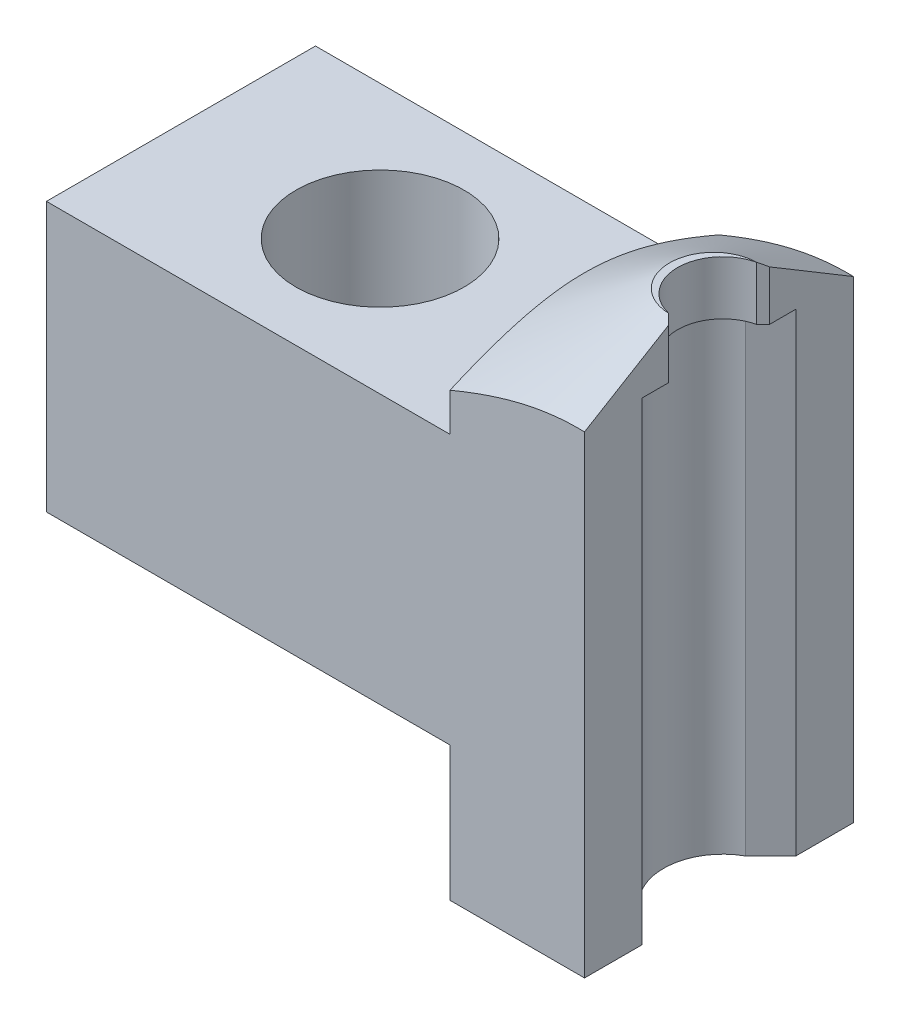
SolidWorks part; units mm, degrees
material "O1 Steel"
ref_plane "Alzado" through (0, 0, 0) normal (0, 0, 1) x (1, 0, 0)
ref_plane "Planta" through (0, 0, 0) normal (0, 1, 0) x (1, 0, 0)
ref_plane "Vista lateral" through (0, 0, 0) normal (1, 0, 0) x (0, 0, -1)
sketch "Croquis1" plane through (0, 0, 0) normal (0, 0, 1) x (1, 0, 0)
  line L0 (-9.525, 6.35) -> (-9.525, -6.35)
  line L1 (-9.525, -6.35) -> (9.525, -6.35)
  line L2 (9.525, -6.35) -> (9.525, -12.7)
  line L3 (9.525, -12.7) -> (15.875, -12.7)
  line L4 (15.875, -12.7) -> (15.875, 12.192)
  line L5 (15.875, 12.192) -> (9.525, 12.192)
  line L7 (9.525, 12.192) -> (9.525, 6.35)
  line L8 (9.525, 6.35) -> (-9.525, 6.35)
  line L9 (-9.525, 0) -> (0, 0) construction
  line L11 (0, 6.35) -> (0, 0) construction
  dimension "D1" = 12.7
  dimension "D2" = 6.35
  dimension "D3" = 25.4
  dimension "D4" = 19.05
  dimension "D7" = 18.542
extrude "Saliente-Extruir1" add sketch "Croquis1" against normal blind 12.7
sketch "Croquis2" plane through (0, 6.35, 0) normal (0, 1, 0) x (1, 0, 0)
  line L0 (-0.127, 6.35) -> (-9.525, 6.35) construction
  line L1 (-9.525, 12.7) -> (-9.525, 0) construction
  line L3 (15.875, 12.7) -> (15.875, 0) construction
  point P0 (-0.127, 6.35)
  dimension "D1" = 16.002
hole_wizard "Refrentado para tornillo con cabeza hueca de #101" positions "Croquis2" profile "Croquis3" counterbore size "#10" standard "Ansi Inch" end condition through all
sketch "Croquis3" plane through (-0.127, 6.35, -6.35) normal (1, 0, 0) x (0, 0, 1)
  line L0 (0, 0) -> (0, 19.05)
  line L1 (0, 19.05) -> (2.5527, 19.05)
  line L3 (2.5527, 19.05) -> (2.5527, 6.35)
  line L4 (2.5527, 6.35) -> (3.9687, 6.35)
  line L5 (3.9687, 6.35) -> (3.9688, 0)
  line L7 (3.9688, 0) -> (0, 0)
  line L11 (0, -6.35) -> (0, 107.95) construction
  dimension "Diámetro de taladro hasta el siguiente" = 5.1054
  dimension "Profundidad de taladro hasta el siguiente" = 19.05
  dimension "Diámetro de refrentado" = 7.9375
  dimension "Profundidad de refrentado" = 6.35
sketch "Croquis6" plane through (0, -12.7, 0) normal (0, -1, 0) x (-1, 0, 0)
  line L0 (-16.0528, 6.35) -> (0.127, 6.35) construction
  line L2 (9.525, 12.7) -> (9.525, 0) construction
  point P0 (-16.0528, 6.35)
  dimension "D1" = 25.5778
hole_wizard "Refrentado para tornillo con cabeza hueca de #61" positions "Croquis6" profile "Croquis7" counterbore size "#6" standard "Ansi Inch" end condition through all
sketch "Croquis7" plane through (16.0528, -12.7, -6.35) normal (1, 0, 0) x (0, 0, -1)
  line L0 (0, 0) -> (0, 24.892)
  line L1 (0, 24.892) -> (2.1336, 24.892)
  line L3 (2.1336, 24.892) -> (2.1336, 22.352)
  line L4 (2.1336, 22.352) -> (2.794, 22.352)
  line L5 (2.794, 22.352) -> (2.794, 0)
  line L7 (2.794, 0) -> (0, 0)
  line L11 (0, -6.35) -> (0, 107.95) construction
  dimension "Diámetro de taladro hasta el siguiente" = 4.2672
  dimension "Profundidad de taladro hasta el siguiente" = 24.892
  dimension "Diámetro de refrentado" = 5.588
  dimension "Profundidad de refrentado" = 22.352
sketch "Croquis12" plane through (0, -12.7, 0) normal (0, -1, 0) x (1, 0, 0)
  line L0 (15.875, -9.978) -> (14.6812, -8.7842)
  line L1 (15.875, -12.7) -> (15.875, -9.1383) construction
  line L2 (14.6812, -8.7842) -> (15.875, -8.7842)
  line L3 (15.875, -9.1383) -> (15.875, -8.4762) construction
  line L4 (15.875, -8.7842) -> (15.875, -9.978)
  line L5 (13.2588, -6.35) -> (-0.127, -6.35) construction
  line L6 (15.875, -3.9158) -> (15.875, -2.722)
  line L7 (14.6812, -3.9158) -> (15.875, -3.9158)
  line L8 (15.875, -2.722) -> (14.6812, -3.9158)
  arc A0 (15.875, -3.5617) -> (15.875, -9.1383) centre (16.0528, -6.35) ccw construction
  arc A1 (15.875, -3.5617) -> (15.875, -9.1383) centre (16.0528, -6.35) ccw construction
  dimension "D1" = 1.1938
  dimension "D2" = 135
extrude "Cortar-Extruir4" cut sketch "Croquis12" against normal up to surface (22.352 mm away) up to face at (14.732, 9.652, -6.35)
sketch "Croquis13" plane through (0, -12.7, 0) normal (0, -1, 0) x (1, 0, 0)
  line L4 (15.875, -3.9669) -> (15.5702, -4.2717)
  line L5 (15.875, -4.2238) -> (15.875, -2.722) construction
  line L6 (15.5702, -4.2717) -> (15.875, -4.2717)
  line L7 (15.875, -4.2717) -> (15.875, -3.9669)
  line L8 (13.9192, -6.35) -> (-0.127, -6.35) construction
  line L9 (15.875, -8.4283) -> (15.875, -8.7331)
  line L10 (15.5702, -8.4283) -> (15.875, -8.4283)
  line L11 (15.875, -8.7331) -> (15.5702, -8.4283)
  arc A1 (15.875, -4.2238) -> (15.875, -8.4762) centre (16.0528, -6.35) ccw construction
  dimension "D1" = 0.3048
  dimension "D2" = 135
extrude "Cortar-Extruir5" cut sketch "Croquis13" against normal through all
ref_plane "Plano1" through (0, 0, -6.35) normal (0, 0, 1) x (1, 0, 0)
sketch "Croquis21" plane through (0, 0, -6.35) normal (0, 0, 1) x (1, 0, 0)
  line L0 (13.5382, 12.192) -> (5.6007, 7.4227)
  line L2 (15.875, -12.7) -> (15.875, 12.192) construction
  line L3 (5.6007, 7.4227) -> (5.6007, 12.192)
  line L4 (5.6007, 12.192) -> (13.5382, 12.192)
  line L5 (15.621, 12.192) -> (15.621, -0.508) construction
  line L6 (15.875, 12.192) -> (9.525, 12.192) construction
  dimension "D1" = 2.3368
  dimension "D2" = 2.0828
  dimension "D3" = 12.7
  dimension "D4" = 31
revolve "Cortar-Revolución12" cut sketch "Croquis21" angle 360 about L5
sketch "Croquis5" plane through (15.875, 0, 0) normal (1, 0, 0) x (0, 0, -1)
  line L1 (8.4727, 12.192) -> (12.7, 9.652)
  line L2 (12.7, 12.192) -> (8.7331, 12.192) construction
  line L6 (12.7, -12.7) -> (12.7, 12.192) construction
  line L7 (12.7, 9.652) -> (12.7, 12.192)
  line L10 (4.2273, 12.192) -> (0, 9.652)
  line L11 (3.9669, 12.192) -> (0, 12.192) construction
  line L12 (0, -12.7) -> (0, 12.192) construction
  line L13 (0, 9.652) -> (0, 12.192)
  line L14 (0, 12.192) -> (4.2273, 12.192)
  line L15 (12.7, 12.192) -> (8.4727, 12.192)
  line L16 (2.722, -12.7) -> (0, -12.7) construction
  dimension "D1" = 31
  dimension "D2" = 22.352
extrude "Cortar-Extruir2" cut sketch "Croquis5" against normal up to surface (6.35 mm away)
